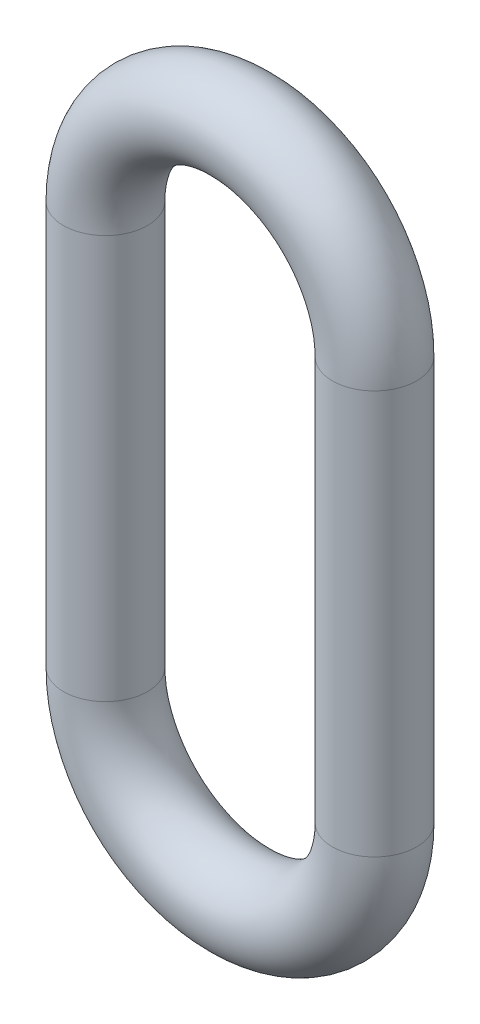
SolidWorks part; units mm, degrees
ref_plane "Спереди" through (0, 0, 0) normal (0, 0, 1) x (1, 0, 0)
ref_plane "Сверху" through (0, 0, 0) normal (0, 1, 0) x (1, 0, 0)
ref_plane "Справа" through (0, 0, 0) normal (1, 0, 0) x (0, 0, -1)
sketch "Эскиз1" plane through (0, 0, 0) normal (0, 0, 1) x (1, 0, 0)
  line L0 (0, 0) -> (0, 24) construction
  line L1 (-8, 0) -> (-8, 24)
  line L2 (8, 0) -> (8, 24)
  arc A0 (-8, 0) -> (8, 0) centre (0, 0) ccw
  arc A1 (8, 24) -> (-8, 24) centre (0, 24) ccw
  point P3 (0, 12)
  dimension "D1" = 40
  dimension "D2" = 16
sketch "Эскиз2" plane through (0, 0, 0) normal (0, 1, 0) x (1, 0, 0)
  line L0 (-8, 0) -> (8, 0) construction
  line L1 (-8, 0) -> (8, 0) construction
  circle A0 centre (-8, 0) radius 2.5
  dimension "D1" = 5
sweep "По траектории1" add profiles "Эскиз2" path "Эскиз1"
sketch "Эскиз3" plane through (0, 0, 0) normal (1, 0, 0) x (0, 0, -1)
  circle A0 centre (0, 29.5) radius 2.5 construction
  circle A1 centre (0, -5.5) radius 2.5 construction
  arc A2 (2.5, -8) -> (-2.5, -8) centre (0, -8) ccw construction
  arc A3 (-2.5, 32) -> (2.5, 32) centre (0, 32) ccw construction
  dimension "D1" = 5
